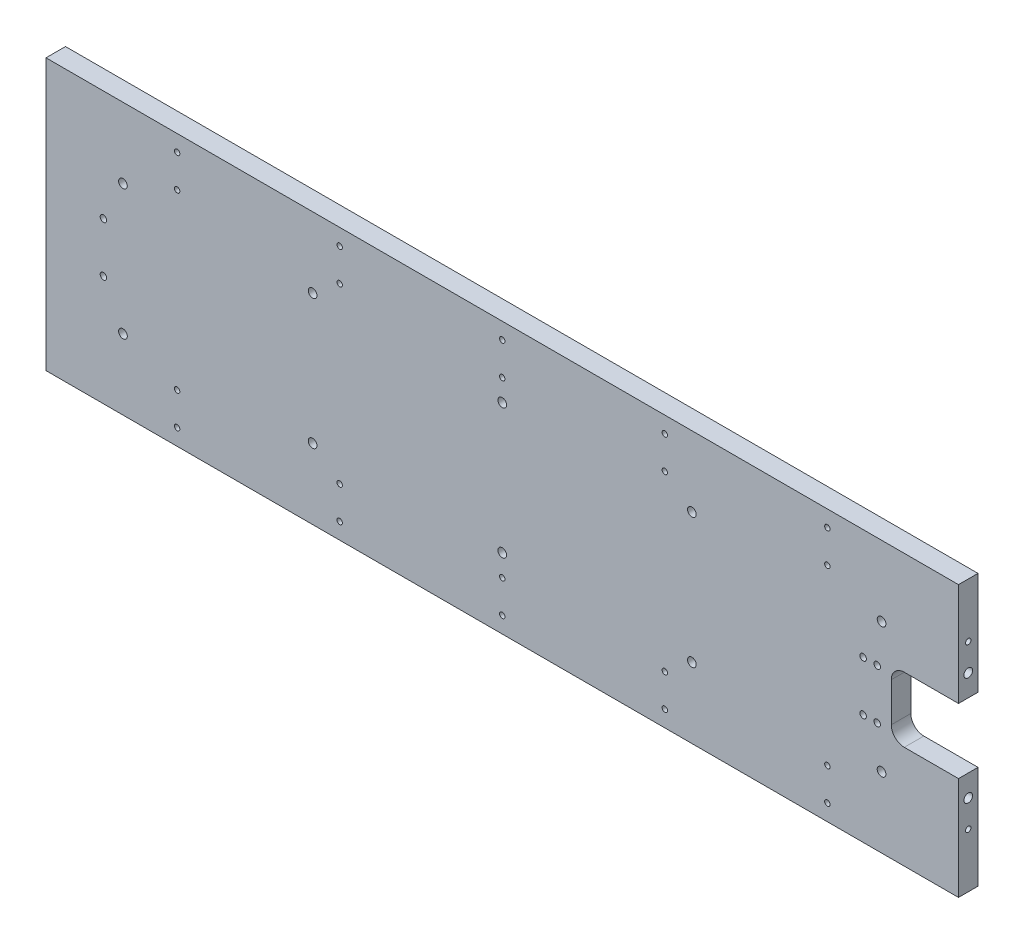
SolidWorks part; units mm, degrees
ref_plane "Front Plane" through (0, 0, 0) normal (0, 0, 1) x (1, 0, 0)
ref_plane "Top Plane" through (0, 0, 0) normal (0, 1, 0) x (1, 0, 0)
ref_plane "Right Plane" through (0, 0, 0) normal (1, 0, 0) x (0, 0, -1)
sketch "Sketch1" plane through (0, 0, 0) normal (0, 0, 1) x (1, 0, 0)
  line L1 (-421, 125) -> (421, 125)
  line L2 (-421, 125) -> (-421, -125)
  line L3 (-421, -125) -> (421, -125)
  line L4 (421, 125) -> (421, -125)
  line L5 (-421, 125) -> (421, -125) construction
  line L6 (-421, -125) -> (421, 125) construction
  point P0 (0, 0)
  dimension "D1" = 842
  dimension "D2" = 250
extrude "Boss-Extrude1" add sketch "Sketch1" along normal blind 18
hole_wizard "Otwory ustalające Ø5.0mm1" positions "Szkic2" profile "Szkic1" hole size "Ø5.0" standard "ISO" end condition through all
sketch "Szkic2" plane through (0, 0, 18) normal (0, 0, 1) x (1, 0, 0)
  point P0 (-300, 110)
  point P3 (-300, 80)
  point P6 (-150, 110)
  point P9 (-150, 80)
  point P12 (0, 110)
  point P15 (0, 80)
  point P18 (150, 110)
  point P21 (150, 80)
  point P24 (300, 110)
  point P27 (300, 80)
  point P30 (-300, -80)
  point P33 (-300, -110)
  point P36 (-150, -80)
  point P39 (-150, -110)
  point P42 (0, -80)
  point P45 (0, -110)
  point P48 (150, -80)
  point P51 (150, -110)
  point P54 (300, -80)
  point P57 (300, -110)
sketch "Szkic1" plane through (-300, 110, 18) normal (1, 0, 0) x (0, -1, 0)
  line L0 (0, 0) -> (0, 18)
  line L1 (0, 18) -> (2.5, 18)
  line L2 (2.5, 18) -> (2.5, 0)
  line L5 (2.5, 0) -> (0, 0)
  line L11 (0, -6.35) -> (0, 107.95) construction
  dimension "Średnica otworu na wylot" = 5
  dimension "Głębokość otworu na wylot" = 18
hole_wizard "Otwory ustalające Ø6.0mm1" positions "Szkic4" profile "Szkic3" hole size "Ø6.0" standard "ISO" end condition through all
sketch "Szkic4" plane through (0, 0, 18) normal (0, 0, 1) x (1, 0, 0)
  point P0 (-368, 23)
  point P3 (-368, -23)
  point P6 (333, 23)
  point P9 (346, 23)
  point P12 (333, -23)
  point P15 (346, -23)
sketch "Szkic3" plane through (-368, 23, 18) normal (1, 0, 0) x (0, -1, 0)
  line L0 (0, 0) -> (0, 18)
  line L1 (0, 18) -> (3, 18)
  line L2 (3, 18) -> (3, 0)
  line L5 (3, 0) -> (0, 0)
  line L11 (0, -6.35) -> (0, 107.95) construction
  dimension "Średnica otworu na wylot" = 6
  dimension "Głębokość otworu na wylot" = 18
hole_wizard "Otwory ustalające Ø8.0mm1" positions "Szkic6" profile "Szkic5" hole size "Ø8.0" standard "ISO" end condition through all
sketch "Szkic6" plane through (0, 0, 18) normal (0, 0, 1) x (1, 0, 0)
  point P0 (-350, 60)
  point P7 (-175, 60)
  point P10 (0, 60)
  point P13 (175, 60)
  point P16 (350, 60)
  point P19 (350, -60)
  point P22 (175, -60)
  point P25 (0, -60)
  point P28 (-175, -60)
  point P31 (-350, -60)
sketch "Szkic5" plane through (-350, 60, 18) normal (1, 0, 0) x (0, -1, 0)
  line L0 (0, 0) -> (0, 18)
  line L1 (0, 18) -> (4, 18)
  line L2 (4, 18) -> (4, 0)
  line L5 (4, 0) -> (0, 0)
  line L11 (0, -6.35) -> (0, 107.95) construction
  dimension "Średnica otworu na wylot" = 8
  dimension "Głębokość otworu na wylot" = 18
hole_wizard "Otwory ustalające Ø5.0mm2" positions "Szkic8" profile "Szkic9" hole size "Ø5.0" standard "ISO"
sketch "Szkic8" plane through (421, 0, 0) normal (1, 0, 0) x (0, 0, -1)
  line L0 (-18, 125) -> (0, 125) construction
  line L1 (-18, -125) -> (0, -125) construction
  line L2 (0, -125) -> (0, 125) construction
  point P0 (-9, 75)
  point P2 (-9, -75)
  dimension "D1" = 50
  dimension "D2" = 50
  dimension "D3" = 9
  dimension "D4" = 9
sketch "Szkic9" plane through (421, 75, 9) normal (0, 1, 0) x (0, 0, -1)
  line L0 (0, 0) -> (0, 46.5022)
  line L1 (0, 46.5022) -> (2.5, 45)
  line L2 (2.5, 45) -> (2.5, 0)
  line L5 (2.5, 0) -> (0, 0)
  line L10 (0, 46.5022) -> (-2.5, 45) construction
  line L11 (0, -6.35) -> (0, 107.95) construction
  dimension "Średnica otworu" = 5
  dimension "Głębokość otworu" = 45
  dimension "Kąt wiertła" = 118
ref_plane "Płaszczyzna1" through (0, 0, 0) normal (-1, 0, 0) x (0, 0, 1)
mirror "Lustro1" about plane through (0, 0, 0) normal (-1, 0, 0) of "Otwory ustalające Ø5.0mm2"
sketch "Szkic10" plane through (0, 0, 18) normal (0, 0, 1) x (1, 0, 0)
  line L0 (421, -125) -> (421, 125) construction
  line L1 (421, 30) -> (371, 30)
  line L2 (421, 30) -> (421, -30)
  line L3 (421, -30) -> (371, -30)
  line L4 (359, 18) -> (359, -18)
  line L5 (421, 125) -> (-421, 125) construction
  arc A0 (371, -30) -> (359, -18) centre (371, -18) cw
  arc A1 (371, 30) -> (359, 18) centre (371, 18) ccw
  point P10 (359, -30)
  point P13 (359, 30)
  dimension "D4" = 12
  dimension "D1" = 62
  dimension "D2" = 95
  dimension "D3" = 60
extrude "Wytnij-wyciągnięcie1" cut sketch "Szkic10" against normal through all contours A1 L4 A0 L3 L2 L1
hole_wizard "Otwór Ø8.0 (8)1" positions "Szkic12" profile "Szkic11" hole size "Ø8.0" standard "ISO"
sketch "Szkic12" plane through (-421, 0, 0) normal (-1, 0, 0) x (0, 0, 1)
  line L0 (18, 125) -> (18, -125) construction
  circle A0 centre (9, 75) radius 2.5 construction
  circle A1 centre (9, -75) radius 2.5 construction
  point P0 (9, 50)
  point P2 (9, -50)
  dimension "D3" = 25
  dimension "D4" = 25
  dimension "D1" = 9
  dimension "D2" = 9
sketch "Szkic11" plane through (-421, 50, 9) normal (0, 1, 0) x (0, 0, 1)
  line L0 (0, 0) -> (0, 24.4034)
  line L1 (0, 24.4034) -> (4, 22)
  line L2 (4, 22) -> (4, 0)
  line L5 (4, 0) -> (0, 0)
  line L10 (0, 24.4034) -> (-4, 22) construction
  line L11 (0, -6.35) -> (0, 107.95) construction
  dimension "Średnica otworu" = 8
  dimension "Głębokość otworu" = 22
  dimension "Kąt wiertła" = 118
mirror "Lustro2" about plane through (0, 0, 0) normal (-1, 0, 0) of "Otwór Ø8.0 (8)1"
